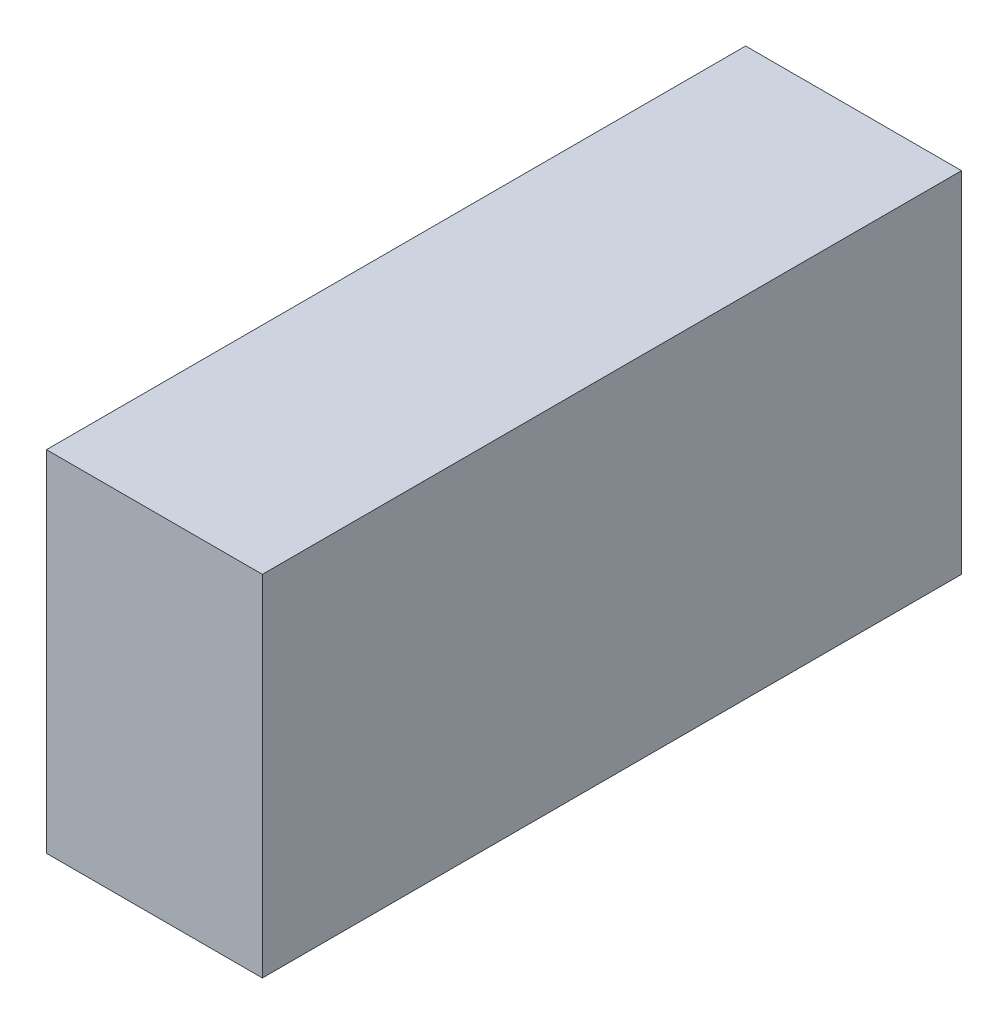
SolidWorks part; units mm, degrees
material "LiPol"
ref_plane "Płaszczyzna przednia" through (0, 0, 0) normal (0, 0, 1) x (1, 0, 0)
ref_plane "Płaszczyzna górna" through (0, 0, 0) normal (0, 1, 0) x (1, 0, 0)
ref_plane "Płaszczyzna prawa" through (0, 0, 0) normal (1, 0, 0) x (0, 0, -1)
sketch "Szkic1" plane through (0, 0, 0) normal (0, 1, 0) x (1, 0, 0)
  line L0 (0, 0) -> (0, 136)
  line L1 (0, 136) -> (42, 136)
  line L2 (42, 136) -> (42, 0)
  line L3 (42, 0) -> (0, 0)
  dimension "D1" = 136
  dimension "D2" = 42
extrude "Dodanie-wyciągnięcie1" add sketch "Szkic1" along normal blind 68
sketch "Szkic2" plane through (0, 0, 0) normal (0, 0, 1) x (1, 0, 0)
  text T0 "\r\n      Battery"
